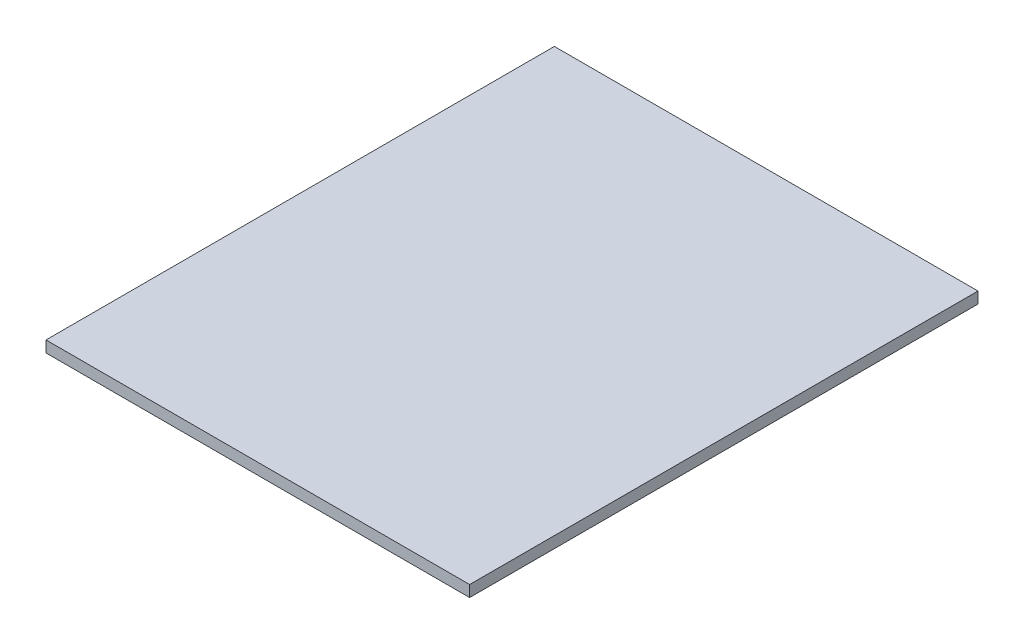
SolidWorks part; units mm, degrees
material "Silicon Rubber"
ref_plane "Front Plane" through (0, 0, 0) normal (0, 0, 1) x (1, 0, 0)
ref_plane "Top Plane" through (0, 0, 0) normal (0, 1, 0) x (1, 0, 0)
ref_plane "Right Plane" through (0, 0, 0) normal (1, 0, 0) x (0, 0, -1)
sketch "Sketch1" plane through (0, 0, 0) normal (0, 1, 0) x (1, 0, 0)
  line L1 (47.625, -57.15) -> (-47.625, -57.15)
  line L2 (47.625, -57.15) -> (47.625, 57.15)
  line L3 (47.625, 57.15) -> (-47.625, 57.15)
  line L4 (-47.625, -57.15) -> (-47.625, 57.15)
  line L5 (47.625, -57.15) -> (-47.625, 57.15) construction
  line L6 (47.625, 57.15) -> (-47.625, -57.15) construction
  point P0 (0, 0)
  dimension "D1" = 95.25
  dimension "D2" = 114.3
extrude "Boss-Extrude1" add sketch "Sketch1" along normal blind 2.54
